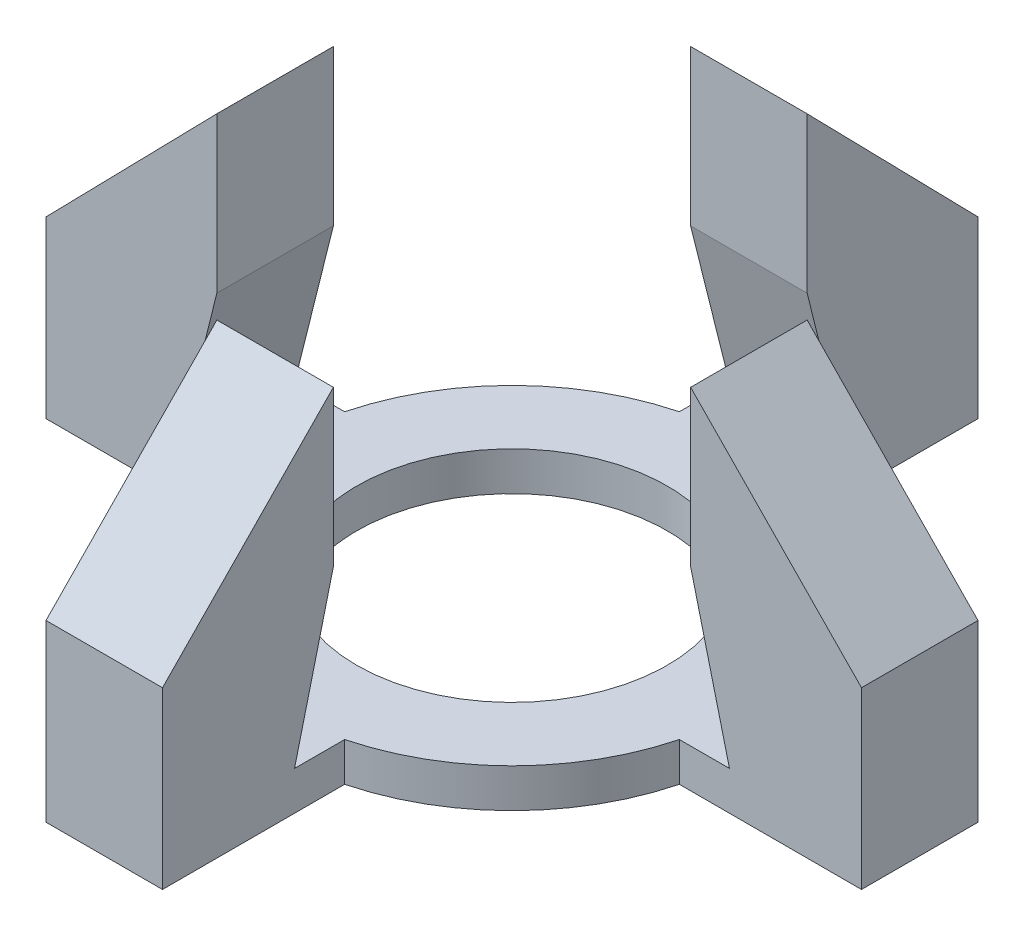
SolidWorks part; units mm, degrees
ref_plane "前视基准面" through (0, 0, 0) normal (0, 0, 1) x (1, 0, 0)
ref_plane "上视基准面" through (0, 0, 0) normal (0, 1, 0) x (1, 0, 0)
ref_plane "右视基准面" through (0, 0, 0) normal (1, 0, 0) x (0, 0, -1)
other "Configuration Table"
sketch "草图1" plane through (0, 0, 0) normal (0, 1, 0) x (1, 0, 0)
  line L0 (-7.5, 52.5) -> (-7.5, 7.5)
  line L1 (-7.5, 7.5) -> (-52.5, 7.5)
  line L2 (-52.5, 7.5) -> (-52.5, -7.5)
  line L3 (-52.5, -7.5) -> (-7.5, -7.5)
  line L4 (-7.5, -7.5) -> (-7.5, -52.5)
  line L5 (-7.5, -52.5) -> (7.5, -52.5)
  line L6 (7.5, -52.5) -> (7.5, -7.5)
  line L7 (7.5, -7.5) -> (52.5, -7.5)
  line L8 (52.5, -7.5) -> (52.5, 7.5)
  line L9 (52.5, 7.5) -> (7.5, 7.5)
  line L10 (7.5, 7.5) -> (7.5, 52.5)
  line L11 (7.5, 52.5) -> (-7.5, 52.5)
  line L12 (-7.5, 52.5) -> (7.5, -52.5) construction
  line L13 (-7.5, -52.5) -> (7.5, 52.5) construction
  circle A0 centre (0, 0) radius 30
  circle A1 centre (0, 0) radius 20
  dimension "D1" = 40
  dimension "D2" = 60
  dimension "D3" = 15
  dimension "D4" = 15
  dimension "D5" = 15
  dimension "D6" = 15
  dimension "D7" = 45
  dimension "D8" = 45
  dimension "D9" = 45
  dimension "D10" = 45
extrude "凸台-拉伸1" add sketch "草图1" along normal blind 5 contours A1 L9 A0 L10 | A1 L7 A0 L9 | A0 L7 L8 L9 | A1 L6 A0 L7 | A0 L4 L5 L6 | A1 L4 A0 L6 | A1 L3 A0 L4 | A1 L1 A0 L3 | A0 L1 L2 L3 | A1 L0 A0 L1 | A1 L10 A0 L0 | A0 L10 L11 L0
sketch "草图4" plane through (0, 5, 0) normal (0, 1, 0) x (1, 0, 0)
  line L0 (-52.5, -7.5) -> (-29.0474, -7.5) construction
  line L1 (-52.5, 7.5) -> (-30.5, 7.5)
  line L2 (-52.5, 7.5) -> (-52.5, -7.5)
  line L3 (-52.5, -7.5) -> (-30.5, -7.5)
  line L4 (-30.5, 7.5) -> (-30.5, -7.5)
  line L5 (-7.5, -52.5) -> (7.5, -52.5)
  line L6 (-7.5, -52.5) -> (-7.5, -30.5)
  line L7 (-7.5, -30.5) -> (7.5, -30.5)
  line L8 (7.5, -52.5) -> (7.5, -30.5)
  line L9 (52.5, -7.5) -> (52.5, 7.5)
  line L10 (52.5, -7.5) -> (30.5, -7.5)
  line L11 (30.5, -7.5) -> (30.5, 7.5)
  line L12 (52.5, 7.5) -> (30.5, 7.5)
  line L13 (7.5, 52.5) -> (-7.5, 52.5)
  line L14 (7.5, 52.5) -> (7.5, 30.5)
  line L15 (7.5, 30.5) -> (-7.5, 30.5)
  line L16 (-7.5, 52.5) -> (-7.5, 30.5)
  line L17 (-52.5, 7.5) -> (52.5, -7.5) construction
  line L18 (52.5, -7.5) -> (52.5, 7.5)
  line L19 (52.5, 7.5) -> (-52.5, -7.5) construction
  point P22 (0, 0)
  line M12 (-7.5, -29.0474) -> (-7.5, -52.5)
  line M13 (-7.5, -52.5) -> (7.5, -52.5)
  line M14 (7.5, -52.5) -> (7.5, -29.0474)
  line M16 (29.0474, -7.5) -> (52.5, -7.5)
  line M17 (52.5, -7.5) -> (52.5, 7.5)
  line M18 (52.5, 7.5) -> (29.0474, 7.5)
  line M20 (7.5, 29.0474) -> (7.5, 52.5)
  line M21 (7.5, 52.5) -> (-7.5, 52.5)
  line M22 (-7.5, 52.5) -> (-7.5, 29.0474)
  line M24 (-29.0474, 7.5) -> (-52.5, 7.5)
  line M25 (-52.5, 7.5) -> (-52.5, -7.5)
  line M26 (-52.5, -7.5) -> (-29.0474, -7.5)
  dimension "D1" = 22
  dimension "D2" = 4
extrude "凸台-拉伸3" add sketch "草图4" along normal blind 40 contours L4 M24 M25 M26 | L15 M20 M21 M22 | L11 M16 M17 M18 | L7 M12 M13 M14
sketch "草图5" plane through (0, 0, 7.5) normal (0, 0, 1) x (1, 0, 0)
  line L0 (-30.5, 5) -> (-52.5, 5)
  line L1 (-52.5, 45) -> (-52.5, 0) construction
  line L2 (-30.5, 25) -> (-35.5, 5)
  line L3 (-30.5, 45) -> (-30.5, 5) construction
  line L4 (-52.5, 22.5) -> (-30.5, 45)
  line L5 (-30.5, 45) -> (-30.5, 25)
  line L6 (-52.5, 22.5) -> (-52.5, 5)
  point P12 (-41.5, 5)
  line M4 (-30.5, 5) -> (-30.5, 45)
  line M5 (-30.5, 45) -> (-52.5, 45)
  line M6 (-52.5, 45) -> (-52.5, 0)
  dimension "D1" = 5
extrude "切除-拉伸1" cut sketch "草图5" against normal up to next contours L4 M6 M5 | L2 L0 M4
sketch "草图6" plane through (-7.5, 0, 0) normal (-1, 0, 0) x (0, 0, 1)
  line L0 (-30.5, 5) -> (-52.5, 5)
  line L1 (-52.5, 45) -> (-52.5, 0) construction
  line L2 (-52.5, 5) -> (-52.5, 22.5)
  line L3 (-52.5, 22.5) -> (-30.5, 45)
  line L4 (-30.5, 45) -> (-30.5, 25)
  line L5 (-30.5, 45) -> (-30.5, 5) construction
  line L6 (-30.5, 25) -> (-35.5, 5)
  line M4 (-30.5, 5) -> (-30.5, 45)
  line M5 (-30.5, 45) -> (-52.5, 45)
  line M6 (-52.5, 45) -> (-52.5, 0)
  dimension "D1" = 5
extrude "切除-拉伸2" cut sketch "草图6" against normal up to next contours L3 M6 M5 | L6 L0 M4
sketch "草图7" plane through (0, 0, -7.5) normal (0, 0, -1) x (-1, 0, 0)
  line L0 (-30.5, 5) -> (-52.5, 5)
  line L3 (-52.5, 45) -> (-52.5, 0) construction
  line L4 (-52.5, 5) -> (-52.5, 22.5)
  line L5 (-52.5, 22.5) -> (-30.5, 45)
  line L6 (-30.5, 45) -> (-30.5, 25)
  line L7 (-30.5, 45) -> (-30.5, 5) construction
  line L8 (-30.5, 25) -> (-35.5, 5)
  line M4 (-30.5, 5) -> (-30.5, 45)
  line M5 (-30.5, 45) -> (-52.5, 45)
  line M6 (-52.5, 45) -> (-52.5, 0)
  dimension "D1" = 5
extrude "切除-拉伸3" cut sketch "草图7" against normal up to next contours L5 M6 M5 | L8 L0 M4
sketch "草图8" plane through (7.5, 0, 0) normal (1, 0, 0) x (0, 0, -1)
  line L0 (-30.5, 5) -> (-52.5, 5)
  line L1 (-52.5, 45) -> (-52.5, 0) construction
  line L2 (-52.5, 5) -> (-52.5, 22.5)
  line L3 (-52.5, 22.5) -> (-30.5, 45)
  line L4 (-30.5, 45) -> (-30.5, 25)
  line L5 (-30.5, 45) -> (-30.5, 5) construction
  line L6 (-30.5, 25) -> (-35.5, 5)
  line M4 (-30.5, 5) -> (-30.5, 45)
  line M5 (-30.5, 45) -> (-52.5, 45)
  line M6 (-52.5, 45) -> (-52.5, 0)
  dimension "D1" = 5
extrude "切除-拉伸4" cut sketch "草图8" against normal up to next contours L3 M6 M5 | L6 L0 M4
